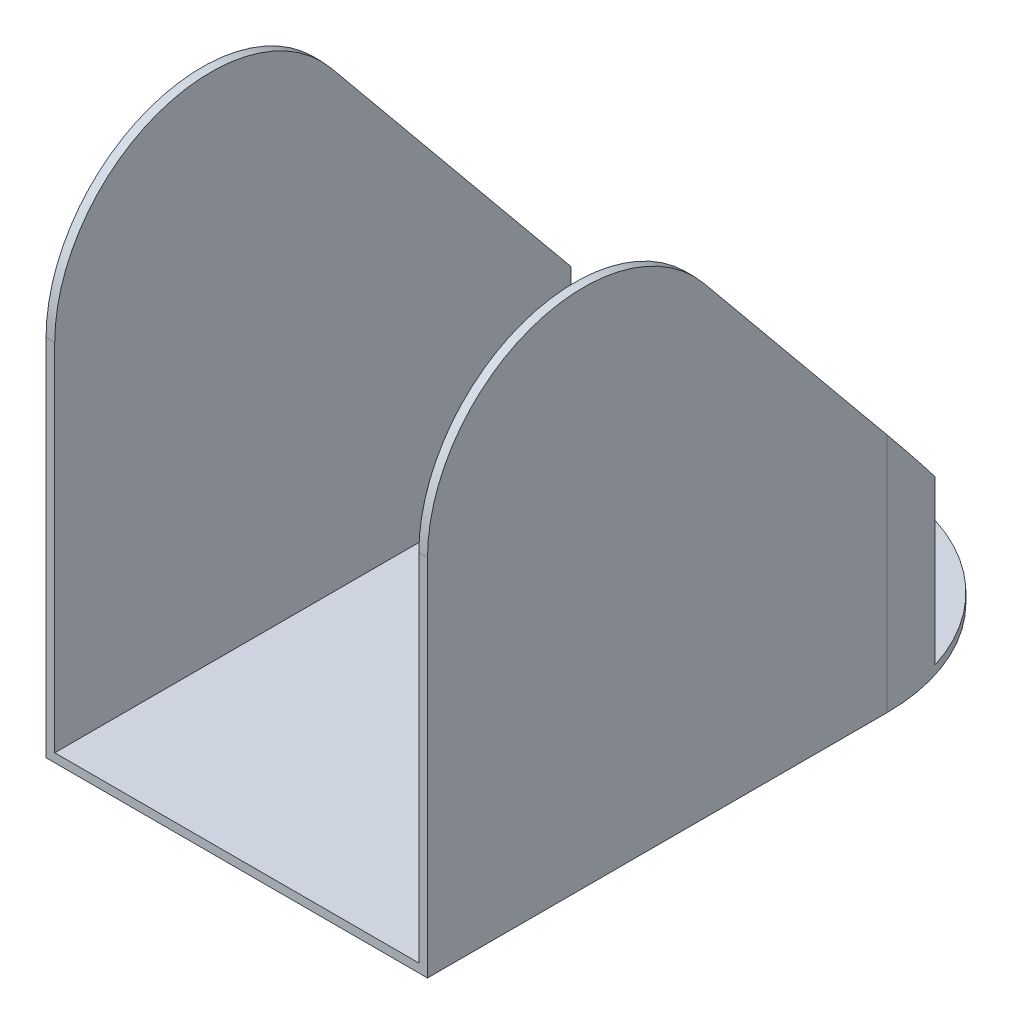
SolidWorks part; units mm, degrees
ref_plane "前视基准面" through (0, 0, 0) normal (0, 0, 1) x (1, 0, 0)
ref_plane "上视基准面" through (0, 0, 0) normal (0, 1, 0) x (1, 0, 0)
ref_plane "右视基准面" through (0, 0, 0) normal (1, 0, 0) x (0, 0, -1)
other "Configuration Table"
sketch "草图1" plane through (0, 0, 0) normal (0, 0, 1) x (1, 0, 0)
  line L0 (21, 30) -> (21, -29)
  line L1 (-22, 30) -> (22, 30) construction
  line L2 (-22, 30) -> (-22, -30)
  line L3 (-22, -30) -> (22, -30)
  line L4 (22, 30) -> (22, -30)
  line L5 (-22, 30) -> (22, -30) construction
  line L6 (-22, -30) -> (22, 30) construction
  line L7 (-21, -29) -> (21, -29)
  line L8 (-21, 30) -> (-21, -29)
  line L9 (-21, 30) -> (-22, 30)
  line L10 (21, 30) -> (22, 30)
  point P0 (0, 0)
  dimension "D1" = 60
  dimension "D2" = 44
  dimension "D3" = 1
extrude "凸台-拉伸1" add sketch "草图1" along normal blind 75
sketch "草图2" plane through (22, 0, 0) normal (1, 0, 0) x (0, 0, -1)
  line L3 (-75, -30) -> (-75, 30) construction
  line L10 (-75, 30) -> (0, 30) construction
  line L11 (0, -30) -> (0, -29) construction
  line L12 (0, -30) -> (0, 30) construction
  line L13 (0, -29) -> (0, 30)
  line L14 (0, 30) -> (-57, 30)
  line L15 (-57, 30) -> (-75, 30)
  line L16 (-75, 30) -> (-75, 12)
  line L17 (0, -29) -> (-43.0945, 23.4296)
  arc A1 (-43.0945, 23.4296) -> (-75, 12) centre (-57, 12) ccw
  line M2 (0, -30) -> (0, 30)
  line M3 (0, 30) -> (-75, 30)
  line M4 (-75, 30) -> (-75, -30)
  dimension "D1" = 36
  dimension "D2" = 1
extrude "切除-拉伸1" cut sketch "草图2" against normal up to surface (44 mm away) contours A1 L17 M2 M3 | A1 M3 M4 up to face at (-22, 0, 37.5)
sketch "草图3" plane through (0, -30, 0) normal (0, -1, 0) x (1, 0, 0)
  line L1 (-22, 0) -> (22, 0) construction
  line L3 (-22, 75) -> (-22, 0) construction
  line L4 (-22, 22) -> (-22, 0)
  line L5 (-22, 0) -> (0, 0)
  line L6 (0, 0) -> (22, 0)
  line L7 (22, 0) -> (22, 22)
  arc A0 (-22, 22) -> (22, 22) centre (0, 22) ccw
  line M1 (-22, 0) -> (22, 0)
  line M2 (22, 0) -> (22, 75)
  line M4 (-22, 75) -> (-22, 0)
extrude "切除-拉伸2" cut sketch "草图3" against normal through all contours A0 M1 M2 | A0 M4 M1
